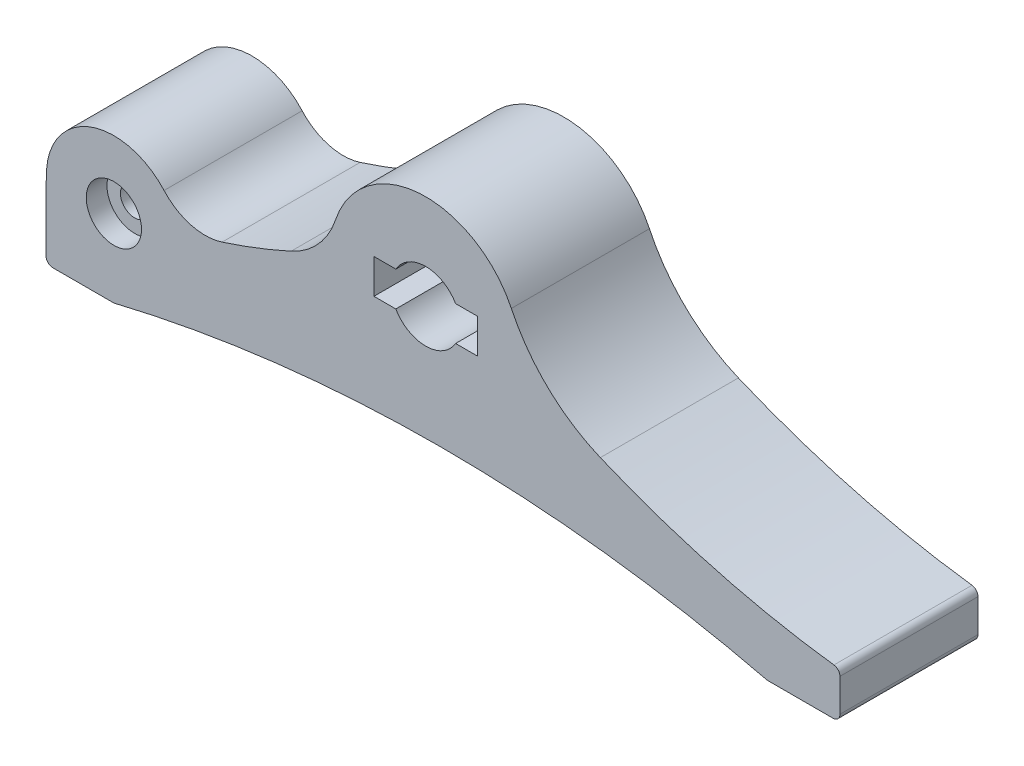
SolidWorks part; units mm, degrees
material "1060 Alloy"
ref_plane "前视基准面" through (0, 0, 0) normal (0, 0, 1) x (1, 0, 0)
ref_plane "上视基准面" through (0, 0, 0) normal (0, 1, 0) x (1, 0, 0)
ref_plane "右视基准面" through (0, 0, 0) normal (1, 0, 0) x (0, 0, -1)
sketch "草图1" plane through (0, 0, 0) normal (0, 0, 1) x (1, 0, 0)
  line L11 (13.751, -0.183) -> (13.751, -0.8199)
  line L14 (-55, -22.1771) -> (-45.17, -22.1771)
  line L15 (60, -15.5424) -> (60, -22.1771)
  line L22 (-55, -11.8528) -> (-55, -22.1771)
  line L24 (49.4815, -22.1771) -> (60, -22.1771)
  line L25 (0, 0) -> (0, -34.4478) construction
  line L26 (-55, -11.8528) -> (-54.9192, -11.5386)
  line L28 (-7.5, 2.5) -> (7.5, 2.5)
  line L29 (-7.5, 2.5) -> (-7.5, -2.5)
  line L30 (-7.5, -2.5) -> (7.5, -2.5)
  line L31 (7.5, 2.5) -> (7.5, -2.5)
  line L32 (-7.5, 2.5) -> (7.5, -2.5) construction
  line L33 (-7.5, -2.5) -> (7.5, 2.5) construction
  arc A1 (13.751, -0.183) -> (-13.7522, 0) centre (0, 0) ccw
  arc A4 (13.751, -0.8199) -> (60, -15.5424) centre (75.8234, 114.1692) ccw
  arc A6 (-45.17, -22.1771) -> (49.4815, -22.1771) centre (2.1557, -218.3834) cw
  arc A7 (-4.3301, -2.5) -> (4.3301, -2.5) centre (0, 0) ccw
  circle A8 centre (-45.17, -10.9429) radius 2.05
  arc A9 (-35.7217, -8.4671) -> (-54.9192, -11.5386) centre (-45.17, -10.9429) ccw
  arc A10 (-13.7522, 0) -> (-35.7217, -8.4671) centre (-58.2787, 82.7966) cw
  arc A11 (4.3301, 2.5) -> (-4.3301, 2.5) centre (0, 0) ccw
  dimension "D1" = 15
  dimension "D2" = 5
  dimension "D3" = 60
  dimension "D4" = 55
extrude "凸台-拉伸1" add sketch "草图1" along normal blind 20 contours A1 A10 A9 L26 L22 L14 A6 L24 L15 A4 L11 A11 L28 L31 L30 A7 L29 A8
fillet "圆角1" radius 12 1 edges at (-13.7522, 0, 10)
fillet "圆角2" radius 8 1 edges at (-35.7217, -8.4671, 10)
fillet "圆角3" radius 1 3 edges at (-55, -22.1771, 10) (60, -22.1771, 10) (60, -15.5424, 10)
fillet "圆角4" radius 25 1 edges at (13.751, -0.8199, 10)
sketch "草图6" plane through (0, 0, 0) normal (0, 0, -1) x (-1, 0, 0)
  circle A1 centre (45.17, -10.9429) radius 4
  dimension "D1" = 8
extrude "切除-拉伸5" cut sketch "草图6" against normal blind 3
sketch "草图7" plane through (0, 0, 0) normal (0, 0, 1) x (1, 0, 0)
  line L0 (-43.5008, -19.025) -> (-33.8928, -19.025) construction
  circle A0 centre (-49.3345, -19.025) radius 1.25
  circle A3 centre (54.7877, -19.025) radius 1.25
  circle A5 centre (34.7343, -16.4202) radius 1.25
  circle A8 centre (-28.0758, -16.4202) radius 1.25
extrude "Cut-Extrude1" cut sketch "草图7" along normal blind 10
sketch "Sketch1" plane through (0, 0, 20) normal (0, 0, 1) x (1, 0, 0)
  circle A1 centre (-45.17, -10.9429) radius 4
extrude "Cut-Extrude2" cut sketch "Sketch1" against normal blind 3
